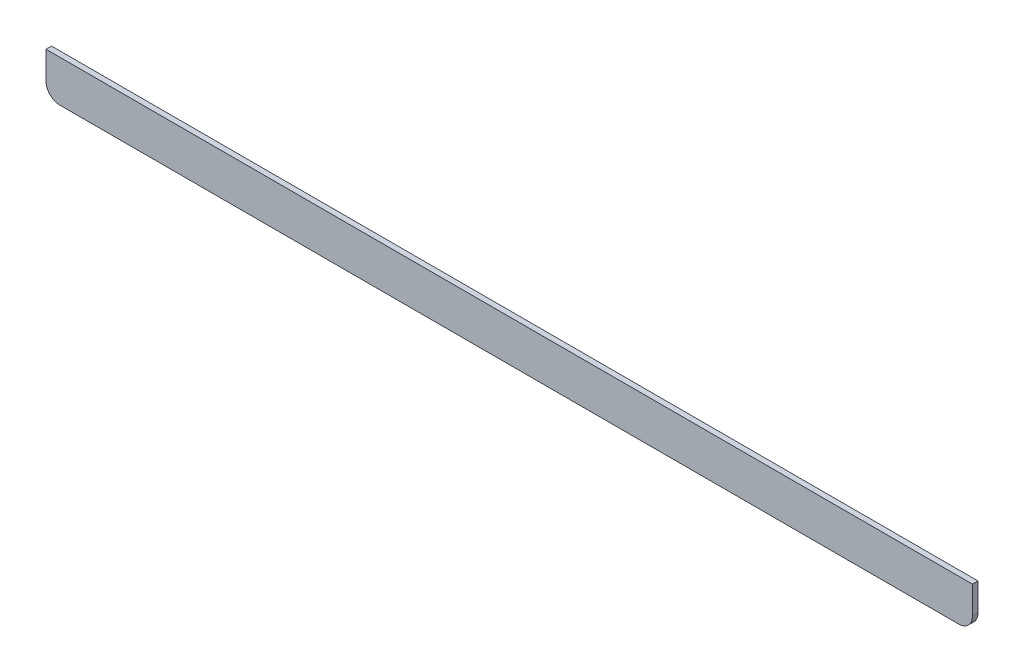
SolidWorks part; units mm, degrees
material "ASTM A36 Steel"
ref_plane "Front Plane" through (0, 0, 0) normal (0, 0, 1) x (1, 0, 0)
ref_plane "Top Plane" through (0, 0, 0) normal (0, 1, 0) x (1, 0, 0)
ref_plane "Right Plane" through (0, 0, 0) normal (1, 0, 0) x (0, 0, -1)
sketch "Sketch1" plane through (0, 0, 0) normal (0, 0, 1) x (1, 0, 0)
  line L1 (-335, -15) -> (335, -15)
  line L2 (-335, -15) -> (-335, 15)
  line L3 (-335, 15) -> (335, 15)
  line L4 (335, -15) -> (335, 15)
  line L5 (-335, -15) -> (335, 15) construction
  line L6 (-335, 15) -> (335, -15) construction
  point P0 (0, 0)
  dimension "D1" = 30
  dimension "D2" = 670
extrude "Boss-Extrude1" add sketch "Sketch1" along normal blind 4
fillet "Fillet1" radius 10 2 edges at (335, -15, 2) (-335, -15, 2)
